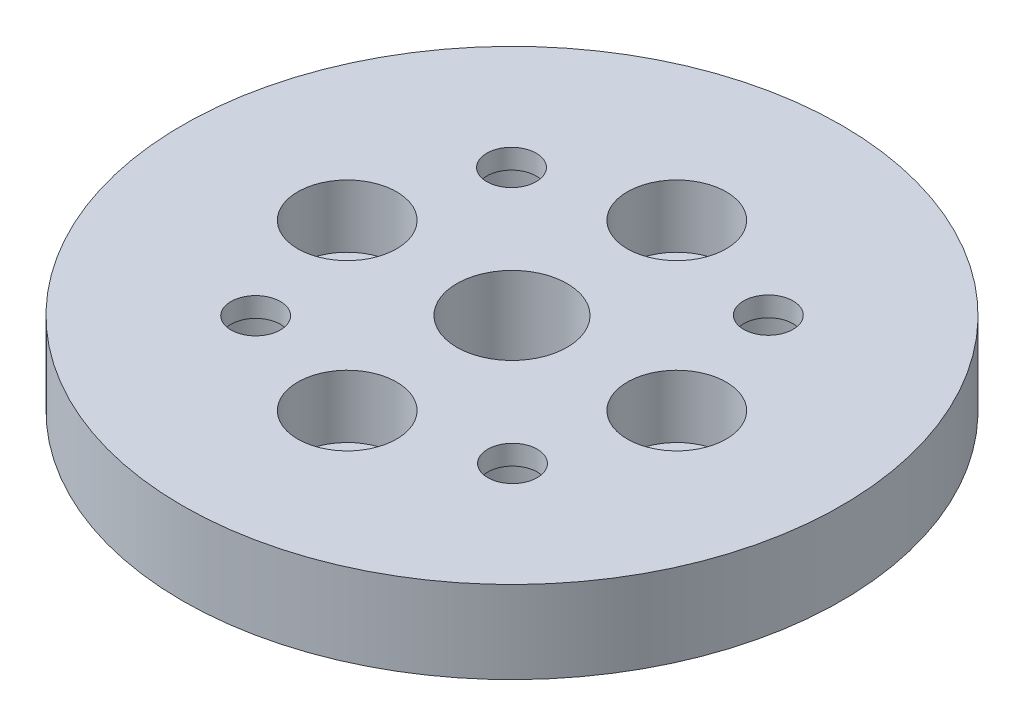
SolidWorks part; units mm, degrees
ref_plane "Front Plane" through (0, 0, 0) normal (0, 0, 1) x (1, 0, 0)
ref_plane "Top Plane" through (0, 0, 0) normal (0, 1, 0) x (1, 0, 0)
ref_plane "Right Plane" through (0, 0, 0) normal (1, 0, 0) x (0, 0, -1)
sketch "Sketch2" plane through (0, 0, 0) normal (0, 1, 0) x (1, 0, 0)
  circle A0 centre (0, 0) radius 20
  dimension "D1" = 40
extrude "Boss-Extrude1" add sketch "Sketch2" along normal blind 5
sketch "Sketch3" plane through (0, 5, 0) normal (0, 1, 0) x (1, 0, 0)
  circle A1 centre (0, 0) radius 3.35
  dimension "D1" = 6.7
extrude "Cut-Extrude1" cut sketch "Sketch3" against normal blind 6
sketch "Sketch4" plane through (0, 5, 0) normal (0, 1, 0) x (1, 0, 0)
  line L0 (0, 0) -> (-20, 0) construction
  circle A0 centre (0, 0) radius 20 construction
  circle A1 centre (0, 10) radius 1.5
  circle A2 centre (10, 0) radius 1.5
  circle A3 centre (0, -10) radius 1.5
  circle A4 centre (-10, 0) radius 1.5
  point P17 (0, 0)
  dimension "D1" = 3
  dimension "D2" = 10
  dimension "D3" = 4
extrude "Cut-Extrude3" cut sketch "Sketch4" against normal blind 6
sketch "Sketch6" plane through (0, 5, 0) normal (0, 1, 0) x (1, 0, 0)
  line L0 (0, 11.5) -> (0, 8.5) construction
  line L1 (0, 8.5) -> (-1.5, 10) construction
  line L2 (-1.5, 10) -> (1.5, 10) construction
  circle A0 centre (0, 10) radius 1.5 construction
  circle A1 centre (0, 10) radius 3
  circle A2 centre (10, 0) radius 3
  circle A3 centre (0, -10) radius 3
  circle A4 centre (-10, 0) radius 3
  point P18 (0, 0)
  dimension "D1" = 6
  dimension "D2" = 4
extrude "Cut-Extrude4" cut sketch "Sketch6" against normal blind 3.8
sketch "Sketch7" plane through (0, 0, 0) normal (0, -1, 0) x (1, 0, 0)
  circle A0 centre (7.7937, 7.7626) radius 1.5
  circle A1 centre (7.7626, -7.7937) radius 1.5
  circle A2 centre (-7.7937, -7.7626) radius 1.5
  circle A3 centre (-7.7626, 7.7937) radius 1.5
  point P11 (0, 0)
  dimension "D1" = 3
  dimension "D3" = 22
  dimension "D2" = 4
extrude "Cut-Extrude5" cut sketch "Sketch7" against normal through all
sketch "Sketch8" plane through (0, 0, 0) normal (0, -1, 0) x (-1, 0, 0)
  line L0 (-6.2937, -7.7626) -> (-9.2937, -7.7626) construction
  line L1 (-9.2937, -7.7626) -> (-7.7937, -9.2626) construction
  line L2 (-7.7937, -9.2626) -> (-7.7937, -6.2626) construction
  circle A0 centre (-7.7937, -7.7626) radius 1.5 construction
  circle A1 centre (-7.7937, -7.7626) radius 3
  circle A2 centre (-7.7626, 7.7937) radius 3
  circle A3 centre (7.7937, 7.7626) radius 3
  circle A4 centre (7.7626, -7.7937) radius 3
  point P18 (0, 0)
  dimension "D1" = 6
  dimension "D2" = 4
extrude "Cut-Extrude6" cut sketch "Sketch8" against normal blind 3.8
